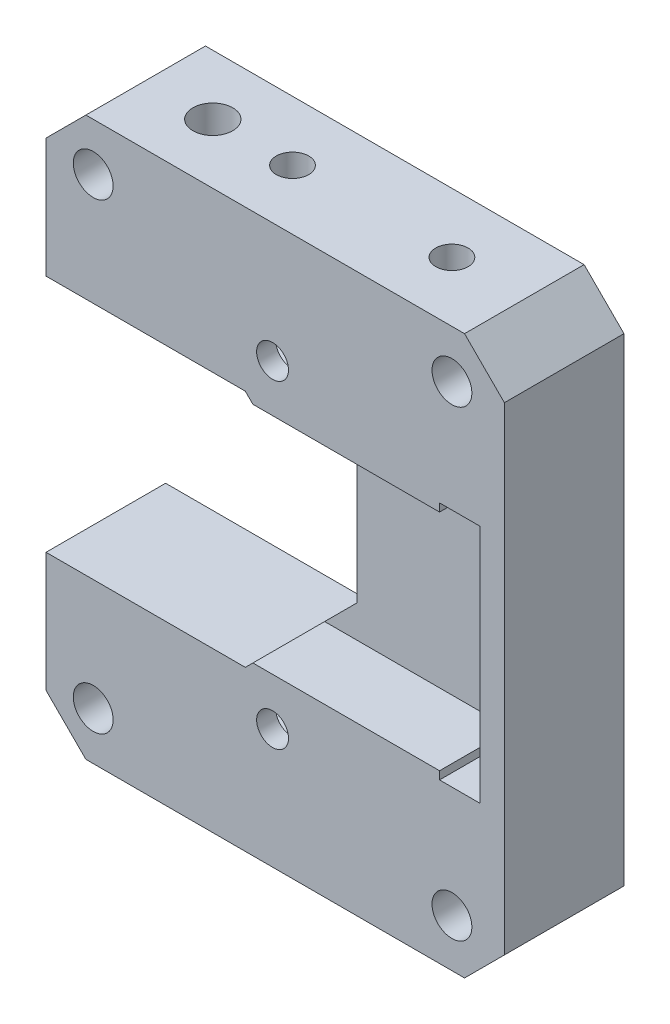
SolidWorks part; units mm, degrees
ref_plane "前基準面" through (0, 0, 0) normal (0, 0, 1) x (1, 0, 0)
ref_plane "上基準面" through (0, 0, 0) normal (0, 1, 0) x (1, 0, 0)
ref_plane "右基準面" through (0, 0, 0) normal (1, 0, 0) x (0, 0, -1)
sketch "草圖1" plane through (0, 0, 0) normal (0, 0, 1) x (1, 0, 0)
  line L0 (-15.9182, 35) -> (-73.4182, 35)
  line L6 (-43.4182, 15) -> (-73.4182, 15)
  line L7 (-73.4182, 15) -> (-73.4182, 35)
  line L37 (-43.4182, 15) -> (-43.4182, -15)
  line L38 (-43.4182, -15) -> (-73.4182, -15)
  line L39 (-73.4182, -15) -> (-73.4182, -35)
  line L40 (-73.4182, -35) -> (-15.9182, -35)
  line L41 (-15.9182, 35) -> (-15.9182, -35)
  point P13 (0, 0)
  dimension "D1" = 20
  dimension "D2" = 57.5
  dimension "D3" = 30
  dimension "D5" = 30
extrude "填料-伸長2" add sketch "草圖1" along normal blind 15
chamfer "導角1" distance 5 angle 45 6 edges at (-15.9182, -35, 7.5) (-73.4182, -35, 7.5) (-43.4182, -15, 7.5) (-43.4182, 15, 7.5) (-73.4182, 35, 7.5) (-15.9182, 35, 7.5)
ref_plane "z平面" through (0, 0, 7.5) normal (0, 0, 1) x (1, 0, 0)
ref_plane "側磁鐵xz平面" through (0, 20, 0) normal (0, 1, 0) x (1, 0, 0)
sketch "草圖16" plane through (-73.4182, 0, 0) normal (-1, 0, 0) x (0, 0, 1)
  line L1 (2.4, 22.6) -> (12.6, 22.6)
  line L2 (2.4, 22.6) -> (2.4, 17.4)
  line L3 (2.4, 17.4) -> (12.6, 17.4)
  line L4 (12.6, 22.6) -> (12.6, 17.4)
  line L7 (7.5, -31.625) -> (7.5, 31.625) construction
  line L8 (8.25, 20) -> (-8.25, 20) construction
  point P4 (2.4, 20)
  point P6 (7.5, 22.6)
  dimension "D1" = 10.2
  dimension "D2" = 5.2
ref_plane "軌道yz平面" through (-60, 0, 0) normal (1, 0, 0) x (0, 0, -1)
extrude "除料-伸長11" cut sketch "草圖16" against normal up to surface (13.4182 mm away)
sketch "草圖17" plane through (-60, 0, 0) normal (1, 0, 0) x (0, 0, -1)
  line L4 (-2.4, 17.4) -> (-2.4, 22.6)
  line L5 (-12.6, 17.4) -> (-2.4, 17.4)
  line L6 (-12.6, 22.6) -> (-12.6, 17.4)
  line L7 (-2.4, 22.6) -> (-12.6, 22.6)
  line L8 (-2.4, 17.4) -> (-2.4, 22.6)
  line L9 (-12.6, 17.4) -> (-2.4, 17.4)
  line L10 (-12.6, 22.6) -> (-12.6, 17.4)
  line L11 (-2.4, 22.6) -> (-12.6, 22.6)
  dimension "D1" = 0
extrude "除料-伸長12" cut sketch "草圖17" along normal blind 15
ref_plane "平面11" through (-45, 0, 0) normal (-1, 0, 0) x (0, 0, 1)
sketch "草圖19" plane through (0, 0, 15) normal (0, 0, 1) x (1, 0, 0)
  line L0 (-45, 2.9588) -> (-45, -2.9588) construction
  line L1 (8.25, 20) -> (-8.25, 20) construction
  circle A0 centre (-45, 20) radius 2
  point P0 (-45, 20)
  dimension "D1" = 4
extrude "除料-伸長13" cut sketch "草圖19" against normal through all
sketch "草圖21" plane through (0, 35, 0) normal (0, 1, 0) x (1, 0, 0)
  line L0 (-31.625, -7.5) -> (31.625, -7.5) construction
  line L1 (-60, -8.25) -> (-60, 8.25) construction
  circle A0 centre (-60, -7.5) radius 2.5
  point P0 (-60, -7.5)
  dimension "D1" = 5
extrude "除料-伸長14" cut sketch "草圖21" against normal up to next
sketch "草圖24" plane through (0, 35, 0) normal (0, 1, 0) x (1, 0, 0)
  line L0 (-31.625, -7.5) -> (31.625, -7.5) construction
  circle A0 centre (-50, -7.5) radius 2.032
  circle A1 centre (-60, -7.5) radius 2.5 construction
  circle A2 centre (-60, -7.5) radius 2.5 construction
  dimension "D1" = 10
extrude "除料-伸長16" cut sketch "草圖24" against normal blind 10 contours A0
pattern_linear "直線複製排列1" count 2 spacing 20 along (1, 0, 0) of "除料-伸長16"
sketch "草圖31" plane through (0, 0, 15) normal (0, 0, 1) x (1, 0, 0)
  line L1 (0, -8.25) -> (0, 8.25) construction
  line L2 (8.25, 0) -> (-8.25, 0) construction
  circle A0 centre (-22.5, 29) radius 2.5
  circle A1 centre (-67.5, 29) radius 2.5
  dimension "D1" = 5
  dimension "D2" = 22.5
  dimension "D3" = 29
  dimension "D4" = 2
extrude "除料-伸長20" cut sketch "草圖31" against normal up to next
mirror "鏡射1" about plane through (0, 0, 0) normal (0, 1, 0) of "除料-伸長20", "除料-伸長11", "除料-伸長12", "除料-伸長13", "除料-伸長14", "除料-伸長16", "直線複製排列1"
sketch "草圖28" plane through (0, 0, 15) normal (0, 0, 1) x (1, 0, 0)
  line L1 (-18.9527, 15.05) -> (-24.0527, 15.05)
  line L2 (-18.9527, 15.05) -> (-18.9527, -15.05)
  line L3 (-18.9527, -15.05) -> (-24.0527, -15.05)
  line L4 (-24.0527, 15.05) -> (-24.0527, -15.05)
  line L5 (8.25, 0) -> (-8.25, 0) construction
  point P6 (-18.9527, 0)
  dimension "D1" = 30.1
  dimension "D2" = 5.1
extrude "除料-伸長18" cut sketch "草圖28" against normal blind 10
sketch "草圖29" plane through (0, 0, 15) normal (0, 0, 1) x (1, 0, 0)
  line L0 (-24.0527, 15.05) -> (-24.0527, -15.05) construction
  line L1 (-24.0527, 14.05) -> (-57.8613, 14.05)
  line L2 (-24.0527, 14.05) -> (-24.0527, -14.05)
  line L3 (-24.0527, -14.05) -> (-57.8613, -14.05)
  line L4 (-57.8613, 14.05) -> (-57.8613, -14.05)
  line L5 (8.25, 0) -> (-8.25, 0) construction
  line L6 (-18.9527, 15.05) -> (-24.0527, 15.05) construction
  point P6 (-57.8613, 0)
  dimension "D1" = 1
extrude "除料-伸長19" cut sketch "草圖29" against normal blind 9
sketch "草圖34" plane through (0, 35, 0) normal (0, 1, 0) x (1, 0, 0)
  line L0 (-20.9182, 0) -> (-68.4182, 0) construction
  line L1 (-68.4182, 0) -> (-68.4182, -15) construction
  line L2 (-20.9182, 0) -> (-68.4182, 0)
  line L3 (-68.4182, 0) -> (-68.4182, -15)
  line L4 (-0.9182, 78.2687) -> (-0.9182, -65.5152) construction
  line L5 (66.5818, 0) -> (66.5818, -15)
  line L6 (19.0818, 0) -> (66.5818, 0)
  line L7 (19.0818, 0) -> (-20.9182, 0)
  line L8 (0, -80) -> (65.3564, -80) construction
  line L9 (-30, -7.5) -> (-60, -7.5) construction
  line L10 (-30, -7.5) -> (-50, -7.5)
  circle A0 centre (58.1636, -7.5) radius 2.5
  circle A1 centre (-50, -7.5) radius 2.032
  circle A2 centre (-50, -7.5) radius 2.032
  circle A3 centre (-30, -7.5) radius 2.032
  circle A4 centre (-30, -7.5) radius 2.032
  circle A5 centre (-60, -7.5) radius 2.5
  circle A6 centre (-60, -7.5) radius 2.5
  circle A7 centre (28.1636, -7.5) radius 2.032
  circle A8 centre (48.1636, -7.5) radius 2.032
  point P24 (-45, -7.5)
  point P25 (-40, -7.5)
  dimension "D4" = 135
  dimension "D5" = 29.0818
  dimension "D6" = 49.0818
  dimension "D7" = 59.0818
  dimension "D8" = 44.0818
  dimension "D9" = 39.0818
  dimension "D1" = 0
  dimension "D2" = 0
  dimension "D3" = 0
sketch "側安裝件" plane through (0, 0, 0) normal (0, 0, -1) x (-1, 0, 0)
  line L0 (0.9182, 0) -> (0.9182, 24.0621) construction
  line L1 (-14.0818, 30) -> (-14.0818, -30) construction
  line L2 (-46.5818, 15) -> (-71.5818, 15)
  line L3 (-41.5818, 10) -> (-46.5818, 15)
  line L4 (-41.5818, -10) -> (-41.5818, 10)
  line L5 (-46.5818, -15) -> (-41.5818, -10)
  line L6 (-71.5818, -15) -> (-46.5818, -15)
  line L7 (-71.5818, -30) -> (-71.5818, -15)
  line L8 (-66.5818, -35) -> (-71.5818, -30)
  line L9 (-19.0818, -35) -> (-66.5818, -35)
  line L10 (-14.0818, -30) -> (-19.0818, -35)
  line L11 (-19.0818, 35) -> (-14.0818, 30)
  line L12 (-66.5818, 35) -> (-19.0818, 35)
  line L13 (-71.5818, 30) -> (-66.5818, 35)
  line L14 (73.4182, 15) -> (73.4182, 30)
  line L15 (73.4182, 30) -> (68.4182, 35)
  line L16 (68.4182, 35) -> (20.9182, 35)
  line L17 (20.9182, 35) -> (15.9182, 30)
  line L18 (15.9182, 30) -> (15.9182, -30)
  line L19 (15.9182, -30) -> (20.9182, -35)
  line L20 (20.9182, -35) -> (68.4182, -35)
  line L21 (68.4182, -35) -> (73.4182, -30)
  line L22 (73.4182, -30) -> (73.4182, -15)
  line L23 (73.4182, -15) -> (48.4182, -15)
  line L24 (48.4182, -15) -> (43.4182, -10)
  line L25 (43.4182, -10) -> (43.4182, 10)
  line L26 (43.4182, 10) -> (48.4182, 15)
  line L27 (48.4182, 15) -> (73.4182, 15)
  line L28 (73.4182, 15) -> (73.4182, 30)
  line L29 (73.4182, 30) -> (68.4182, 35)
  line L30 (68.4182, 35) -> (20.9182, 35)
  line L31 (20.9182, 35) -> (15.9182, 30)
  line L32 (15.9182, 30) -> (15.9182, -30) construction
  line L33 (15.9182, -30) -> (20.9182, -35)
  line L34 (20.9182, -35) -> (68.4182, -35)
  line L35 (68.4182, -35) -> (73.4182, -30)
  line L36 (73.4182, -30) -> (73.4182, -15)
  line L37 (73.4182, -15) -> (48.4182, -15)
  line L38 (48.4182, -15) -> (43.4182, -10)
  line L39 (43.4182, -10) -> (43.4182, 10)
  line L40 (43.4182, 10) -> (48.4182, 15)
  line L41 (48.4182, 15) -> (73.4182, 15)
  line L42 (-71.5818, 15) -> (-71.5818, 30)
  line L43 (-14.0818, 30) -> (15.9182, 30)
  line L44 (-14.0818, -30) -> (15.9182, -30)
  line L45 (8.25, 0) -> (-8.25, 0) construction
  circle A0 centre (-20.6636, 29) radius 2.5 construction
  circle A1 centre (45, 20) radius 2 construction
  circle A2 centre (67.5, 29) radius 2.5 construction
  circle A3 centre (22.5, -29) radius 2.5 construction
  circle A4 centre (45, -20) radius 2 construction
  circle A5 centre (67.5, -29) radius 2.5 construction
  circle A6 centre (45, 20) radius 2 construction
  circle A7 centre (67.5, 29) radius 2.5 construction
  circle A8 centre (22.5, -29) radius 2.5 construction
  circle A9 centre (45, -20) radius 2 construction
  circle A10 centre (67.5, -29) radius 2.5 construction
  circle A11 centre (67.5, 29) radius 3
  circle A12 centre (22.5, 29) radius 2.5 construction
  circle A13 centre (22.5, 29) radius 2.5 construction
  circle A14 centre (22.5, 29) radius 3
  circle A15 centre (22.5, -29) radius 3
  circle A16 centre (67.5, -29) radius 3
  circle A17 centre (-65.6636, -29) radius 2.5 construction
  circle A18 centre (-43.1636, -20) radius 2 construction
  circle A19 centre (-20.6636, -29) radius 2.5 construction
  circle A20 centre (-65.6636, 29) radius 2.5 construction
  circle A21 centre (-43.1636, 20) radius 2 construction
  circle A22 centre (-65.6636, -29) radius 3
  circle A23 centre (-20.6636, -29) radius 3
  circle A24 centre (-20.6636, 29) radius 3
  circle A25 centre (-65.6636, 29) radius 3
  point P71 (-71.5818, 35)
  dimension "D2" = 6
  dimension "D3" = 29
  dimension "D4" = 45
  dimension "D5" = 21.5818
  dimension "D6" = 72.5
  dimension "D7" = 60
  dimension "D8" = 70
  dimension "D9" = 15
  dimension "D10" = 25
  dimension "D11" = 20
  dimension "D12" = 57.5
  dimension "D13" = 5
  dimension "D14" = 30
  dimension "D15" = 58
  dimension "D16" = 44.0818
  dimension "D17" = 20
  dimension "D1" = 0
